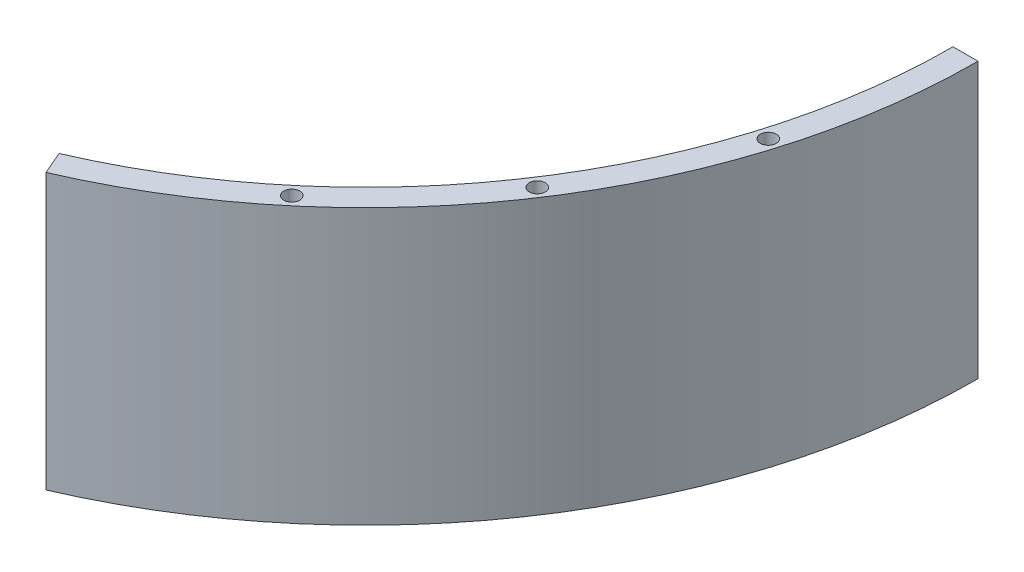
SolidWorks part; units mm, degrees
ref_plane "正面" through (0, 0, 0) normal (0, 0, 1) x (1, 0, 0)
ref_plane "平面" through (0, 0, 0) normal (0, 1, 0) x (1, 0, 0)
ref_plane "右側面" through (0, 0, 0) normal (1, 0, 0) x (0, 0, -1)
sketch "ｽｹｯﾁ1" plane through (0, 0, 0) normal (0, 1, 0) x (1, 0, 0)
  line L0 (0, 0) -> (122.5, 0) construction
  line L1 (0, 0) -> (48.5721, -112.4589) construction
  line L2 (117.5, 0) -> (122.5, 0)
  line L3 (46.5896, -107.8687) -> (48.5721, -112.4589)
  arc A0 (48.5721, -112.4589) -> (122.5, 0) centre (0, 0) ccw
  arc A1 (46.5896, -107.8687) -> (117.5, 0) centre (0, 0) ccw
  dimension "D1" = 245
  dimension "D2" = 5
  dimension "D3" = 66.64
extrude "ﾎﾞｽ - 押し出し1" add sketch "ｽｹｯﾁ1" along normal blind 55
sketch "ｽｹｯﾁ3" plane through (0, 55, 0) normal (0, 1, 0) x (1, 0, 0)
  line L0 (48.5721, -112.4589) -> (0, 0) construction
  line L1 (122.5, 0) -> (0, 0) construction
  line L2 (122.5, 0) -> (117.5, 0) construction
  line L3 (78.7742, -93.813) -> (0, 0) construction
  line L4 (0, 0) -> (117.3578, -35.1197) construction
  line L5 (0, 0) -> (102.3629, -67.291) construction
  line L6 (48.5721, -112.4589) -> (78.7742, -93.813) construction
  line L8 (78.7742, -93.813) -> (102.3629, -67.291) construction
  line L9 (102.3629, -67.291) -> (117.3578, -35.1197) construction
  line L10 (117.3578, -35.1197) -> (122.5, 0) construction
  arc A0 (48.5721, -112.4589) -> (122.5, 0) centre (0, 0) ccw construction
  arc A1 (47.5808, -110.1638) -> (120, 0) centre (0, 0) ccw construction
  circle A2 centre (77.1666, -91.8984) radius 1.6
  circle A3 centre (100.2739, -65.9177) radius 1.6
  circle A4 centre (114.9627, -34.403) radius 1.6
  point P13 (120, 0)
  dimension "D1" = 3.2
extrude "ｶｯﾄ - 押し出し1" cut sketch "ｽｹｯﾁ3" against normal blind 10
